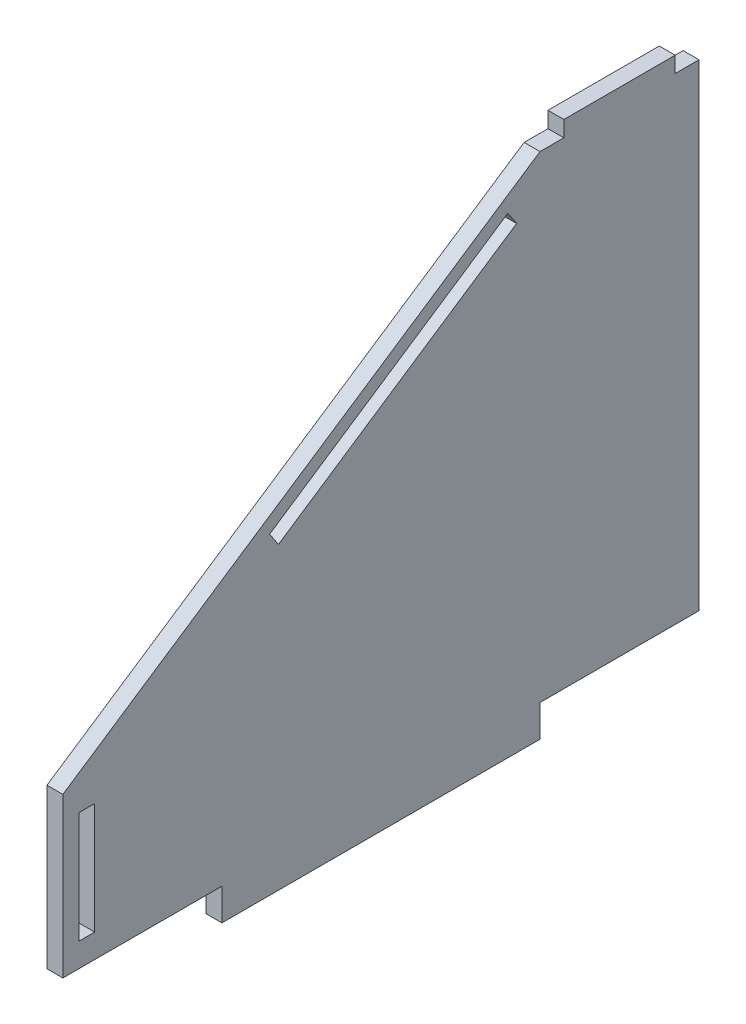
SolidWorks part; units mm, degrees
ref_plane "Alzado" through (0, 0, 0) normal (0, 0, 1) x (1, 0, 0)
ref_plane "Planta" through (0, 0, 0) normal (0, 1, 0) x (1, 0, 0)
ref_plane "Vista lateral" through (0, 0, 0) normal (1, 0, 0) x (0, 0, -1)
sketch "Croquis1" plane through (0, 0, 0) normal (1, 0, 0) x (0, 0, -1)
  line L0 (150, 150) -> (0, 50)
  line L1 (0, 0) -> (50, 0)
  line L2 (0, 0) -> (0, 50)
  line L3 (150, 150) -> (157.5, 150)
  line L4 (200, 0) -> (200, 150)
  line L6 (5, 42.5) -> (10, 42.5)
  line L7 (5, 42.5) -> (5, 7.5)
  line L8 (5, 7.5) -> (10, 7.5)
  line L9 (50, 0) -> (50, -10)
  line L10 (50, -10) -> (150, -10)
  line L11 (150, 0) -> (150, -10)
  line L12 (10, 42.5) -> (10, 7.5)
  line L13 (192.5, 150) -> (200, 150)
  line L14 (150, 0) -> (200, 0)
  line L15 (65, 88.3333) -> (139.8845, 138.2564)
  line L16 (157.5, 150) -> (157.5, 155)
  line L17 (157.5, 155) -> (192.5, 155)
  line L18 (192.5, 150) -> (192.5, 155)
  line L19 (139.8845, 138.2564) -> (142.658, 134.0961)
  line L20 (142.658, 134.0961) -> (67.7735, 84.1731)
  line L21 (67.7735, 84.1731) -> (65, 88.3333)
  line L22 (5, 53.3333) -> (5, 0) construction
  line L23 (65, 88.3333) -> (5, 48.3333) construction
  dimension "D6" = 35
  dimension "D10" = 7.5
  dimension "D1" = 150
  dimension "D2" = 200
  dimension "D3" = 50
  dimension "D4" = 50
  dimension "D5" = 7.5
  dimension "D7" = 100
  dimension "D8" = 50
  dimension "D9" = 10
  dimension "D11" = 5
  dimension "D31" = 35
  dimension "D32" = 5
  dimension "D33" = 90
  dimension "D34" = 15
  dimension "D35" = 5
  dimension "D36" = 5
  dimension "D37" = 35
extrude "Saliente-Extruir1" add sketch "Croquis1" along normal blind 5
